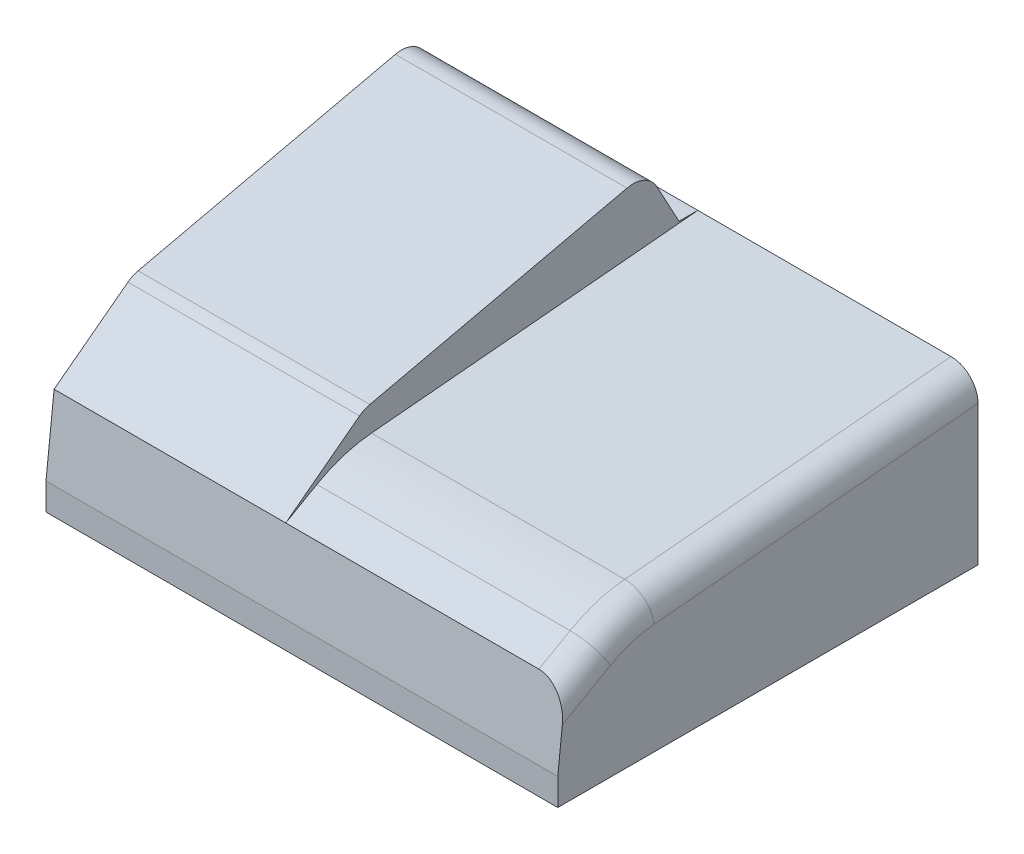
SolidWorks part; units mm, degrees
ref_plane "Front Plane" through (0, 0, 0) normal (0, 0, 1) x (1, 0, 0)
ref_plane "Top Plane" through (0, 0, 0) normal (0, 1, 0) x (1, 0, 0)
ref_plane "Right Plane" through (0, 0, 0) normal (1, 0, 0) x (0, 0, -1)
sketch "Sketch1" plane through (0, 0, 0) normal (0, 1, 0) x (1, 0, 0)
  line L1 (-95, -78) -> (95, -78)
  line L2 (-95, -78) -> (-95, 78)
  line L3 (-95, 78) -> (95, 78)
  line L4 (95, -78) -> (95, 78)
  line L5 (-95, -78) -> (95, 78) construction
  line L6 (-95, 78) -> (95, -78) construction
  point P0 (0, 0)
  dimension "D1" = 190
  dimension "D2" = 156
extrude "Boss-Extrude1" add sketch "Sketch1" along normal blind 84
sketch "Sketch2" plane through (-95, 0, 0) normal (-1, 0, 0) x (0, 0, 1)
  line L0 (-78, 62) -> (-71, 62)
  line L1 (-71, 62) -> (-59.1186, 84)
  line L2 (-59.1186, 84) -> (45.8814, 60)
  line L3 (45.8814, 60) -> (75, 38)
  line L4 (-78, 0) -> (78, 0)
  line L5 (78, 0) -> (78, 84)
  line L6 (78, 84) -> (-78, 84)
  line L7 (-78, 84) -> (-78, 0)
  line L8 (-78, 0) -> (78, 0)
  line L9 (78, 0) -> (78, 84)
  line L10 (78, 84) -> (-78, 84)
  line L11 (-78, 84) -> (-78, 0)
  line L12 (75, 38) -> (78, 10)
  line M8 (78, 84) -> (-78, 84)
  line M9 (-78, 84) -> (-78, 0)
  dimension "D2" = 7
  dimension "D3" = 62
  dimension "D4" = 105
  dimension "D5" = 60
  dimension "D6" = 38
  dimension "D7" = 3
  dimension "D8" = 10
  dimension "D1" = 0
extrude "Cut-Extrude1" cut sketch "Sketch2" against normal through all contours L0 L1 M8 M9 | L3 L12 L9 L2 M8
sketch "Sketch3" plane through (95, 0, 0) normal (1, 0, 0) x (0, 0, -1)
  line L0 (78, 62) -> (-54, 50)
  line L1 (-54, 50) -> (-75, 38)
  line L8 (71, 62) -> (59.1186, 84)
  line L9 (59.1186, 84) -> (-45.8814, 60)
  line L10 (-45.8814, 60) -> (-75, 38)
  line L11 (-75, 38) -> (-78, 10)
  line L12 (-78, 10) -> (-78, 0)
  line L13 (-78, 0) -> (78, 0)
  line L14 (78, 0) -> (78, 62)
  line L15 (78, 62) -> (71, 62)
  line L16 (71, 62) -> (59.1186, 84)
  line L17 (59.1186, 84) -> (-45.8814, 60)
  line L18 (-45.8814, 60) -> (-75, 38)
  line L19 (-75, 38) -> (-78, 10)
  line L20 (-78, 10) -> (-78, 0)
  line L21 (-78, 0) -> (78, 0)
  line L22 (78, 0) -> (78, 62)
  line L23 (78, 62) -> (71, 62)
  line M9 (71, 62) -> (59.1186, 84)
  line M10 (59.1186, 84) -> (-45.8814, 60)
  line M11 (-45.8814, 60) -> (-75, 38)
  line M16 (78, 62) -> (71, 62)
  dimension "D2" = 50
  dimension "D3" = 21
  dimension "D1" = 0
extrude "Cut-Extrude2" cut sketch "Sketch3" against normal blind 104 contours L1 L0 M16 M9 M10 M11
fillet "Fillet1" radius 50 1 edges at (43, 50, 54)
fillet "Fillet2" radius 10 1 edges at (-52, 84, -59.1186)
fillet "Fillet3" radius 10 4 edges at (95, 41.3012, 69.2229) (95, 48.8841, 53.6488) (95, 56.4925, -17.4172) (-52, 60, 45.8814)
